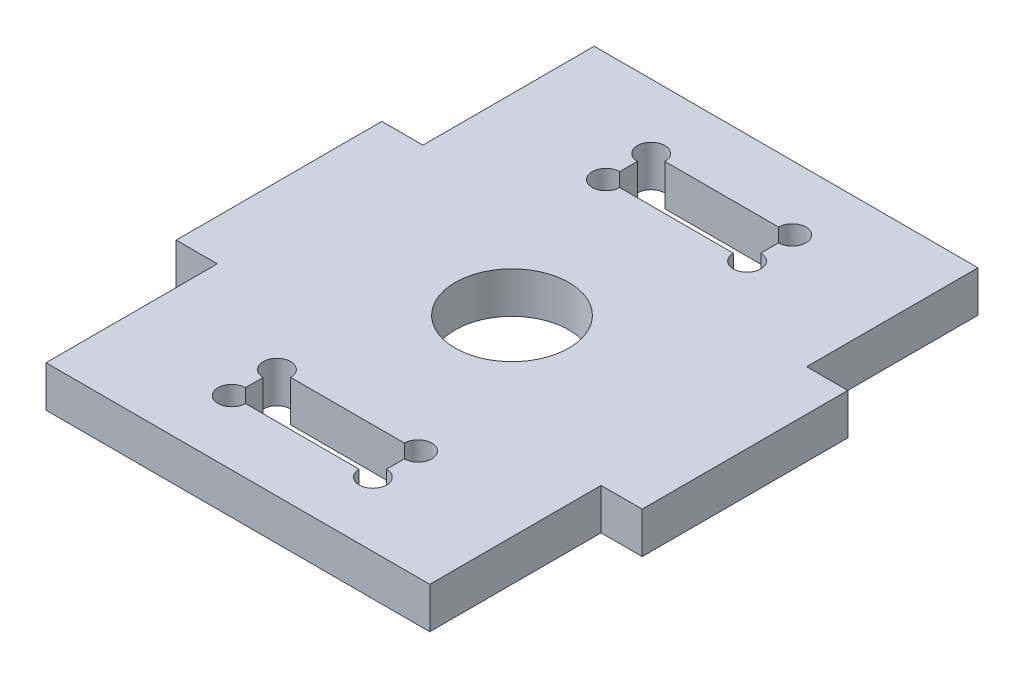
SolidWorks part; units mm, degrees
ref_plane "前视基准面" through (0, 0, 0) normal (0, 0, 1) x (1, 0, 0)
ref_plane "上视基准面" through (0, 0, 0) normal (0, 1, 0) x (1, 0, 0)
ref_plane "右视基准面" through (0, 0, 0) normal (1, 0, 0) x (0, 0, -1)
other "Configuration Table"
sketch "草图1" plane through (0, 0, 0) normal (0, 1, 0) x (1, 0, 0)
  line L0 (-14.137, 0) -> (13.8082, 0) construction
  line L1 (-14, 20) -> (14, 20)
  line L2 (-14, 20) -> (-14, -20)
  line L3 (-14, -20) -> (14, -20)
  line L4 (14, 20) -> (14, -20)
  line L5 (-14, 20) -> (14, -20) construction
  line L6 (-14, -20) -> (14, 20) construction
  line L7 (-5.15, 15.3) -> (5.15, 15.3)
  line L8 (-5.15, 15.3) -> (-5.15, 12)
  line L9 (-5.15, 12) -> (5.15, 12)
  line L10 (5.15, 15.3) -> (5.15, 12)
  line L11 (-5.15, 15.3) -> (5.15, 12) construction
  line L12 (-5.15, 12) -> (5.15, 15.3) construction
  line L13 (-5.15, -12) -> (5.15, -12)
  line L14 (5.15, -15.3) -> (5.15, -12)
  line L15 (-5.15, -15.3) -> (5.15, -15.3)
  line L16 (-5.15, -15.3) -> (-5.15, -12)
  line L17 (0, 4.1878) -> (0, -3.9164) construction
  line L18 (-14, -7.5) -> (-17, -7.5)
  line L19 (-14, -7.5) -> (-14, 7.5)
  line L20 (-14, 7.5) -> (-17, 7.5)
  line L21 (-17, -7.5) -> (-17, 7.5)
  line L22 (14, 7.5) -> (17, 7.5)
  line L23 (17, -7.5) -> (17, 7.5)
  line L24 (14, -7.5) -> (17, -7.5)
  line L25 (14, -7.5) -> (14, 7.5)
  circle A0 centre (-5.15, 15.3) radius 1
  circle A1 centre (5.15, 15.3) radius 1
  circle A2 centre (5.15, 12) radius 1
  circle A3 centre (-5.15, 12) radius 1
  circle A4 centre (5.15, -12) radius 1
  circle A5 centre (5.15, -15.3) radius 1
  circle A6 centre (-5.15, -12) radius 1
  circle A7 centre (-5.15, -15.3) radius 1
  point P0 (0, 0)
  point P6 (0, 13.65)
  point P29 (-17, 0)
  dimension "D6" = 2
  dimension "D1" = 28
  dimension "D2" = 40
  dimension "D3" = 3.3
  dimension "D4" = 10.3
  dimension "D5" = 12
  dimension "D7" = 3
  dimension "D8" = 15
extrude "凸台-拉伸1" add sketch "草图1" along normal blind 3 contours L4 L1 L2 L3 A3 L8 A0 L7 A1 L10 A2 L9 L15 A7 L16 A6 L13 A4 L14 A5 | L21 L18 L2 L20 | L4 L24 L23 L22
sketch "草图2" plane through (0, 3, 0) normal (0, 1, 0) x (1, 0, 0)
  line L0 (-17, -7.5) -> (-17, 7.5) construction
  line L1 (-29, 1.5) -> (-5, 1.5)
  line L2 (-29, 1.5) -> (-29, -1.5)
  line L3 (-29, -1.5) -> (-5, -1.5)
  line L4 (-5, 1.5) -> (-5, -1.5)
  line L5 (-29, 1.5) -> (-5, -1.5) construction
  line L6 (-29, -1.5) -> (-5, 1.5) construction
  line L7 (-17, 0) -> (-9.5, 0) construction
  line L8 (0, 5.2735) -> (0, -3.4511) construction
  line L9 (-11, 3) -> (-8, 3)
  line L10 (-11, 3) -> (-11, -3)
  line L11 (-11, -3) -> (-8, -3)
  line L12 (-8, 3) -> (-8, -3)
  line L13 (-11, 3) -> (-8, -3) construction
  line L14 (-11, -3) -> (-8, 3) construction
  line L15 (11, -3) -> (8, 3) construction
  line L16 (11, 3) -> (8, -3) construction
  line L17 (17, 0) -> (9.5, 0) construction
  line L18 (29, -1.5) -> (5, 1.5) construction
  line L19 (29, 1.5) -> (5, -1.5) construction
  line L20 (8, 3) -> (8, -3)
  line L21 (11, -3) -> (8, -3)
  line L22 (11, 3) -> (11, -3)
  line L23 (11, 3) -> (8, 3)
  line L24 (5, 1.5) -> (5, -1.5)
  line L25 (29, -1.5) -> (5, -1.5)
  line L26 (29, 1.5) -> (29, -1.5)
  line L27 (29, 1.5) -> (5, 1.5)
  point P0 (-17, 0)
  point P26 (17, 0)
  dimension "D1" = 24
  dimension "D2" = 3
  dimension "D3" = 3
  dimension "D4" = 6
  dimension "D5" = 6
sketch "草图3" plane through (0, 3, 0) normal (0, 1, 0) x (1, 0, 0)
  circle A0 centre (0, 0) radius 4.15
  dimension "D1" = 8.3
extrude "切除-拉伸2" cut sketch "草图3" against normal blind 3
